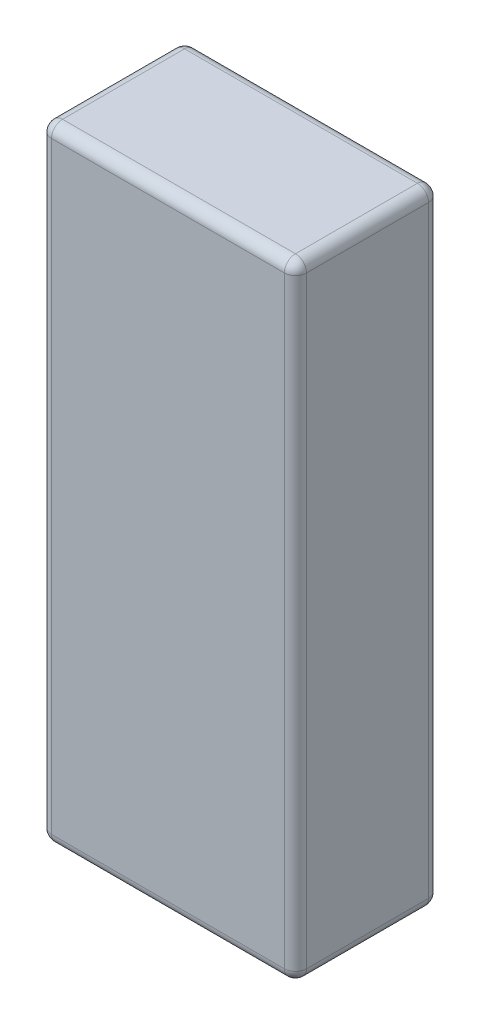
SolidWorks part; units mm, degrees
ref_plane "Front Plane" through (0, 0, 0) normal (0, 0, 1) x (1, 0, 0)
ref_plane "Top Plane" through (0, 0, 0) normal (0, 1, 0) x (1, 0, 0)
ref_plane "Right Plane" through (0, 0, 0) normal (1, 0, 0) x (0, 0, -1)
sketch "Sketch1" plane through (0, 0, 0) normal (0, 0, 1) x (1, 0, 0)
  line L1 (-34.5, -84.5) -> (34.5, -84.5)
  line L2 (-34.5, -84.5) -> (-34.5, 84.5)
  line L3 (-34.5, 84.5) -> (34.5, 84.5)
  line L4 (34.5, -84.5) -> (34.5, 84.5)
  line L5 (-34.5, -84.5) -> (34.5, 84.5) construction
  line L6 (-34.5, 84.5) -> (34.5, -84.5) construction
  point P0 (0, 0)
  dimension "D1" = 69
  dimension "D2" = 169
extrude "Boss-Extrude1" add sketch "Sketch1" along normal mid plane 39
sketch "Sketch2" plane through (0, 0, 0) normal (1, 0, 0) x (0, 0, -1)
  line L0 (-19.5, 84.5) -> (19.5, -84.5) construction
fillet "Fillet1" radius 3 12 edges at (-34.5, 0, 19.5) (-34.5, 0, -19.5) (34.5, 0, 19.5) (34.5, 0, -19.5) (-34.5, -84.5, 0) (0, -84.5, 19.5) (34.5, -84.5, 0) (0, -84.5, -19.5) (34.5, 84.5, 0) (0, 84.5, 19.5) (-34.5, 84.5, 0) (0, 84.5, -19.5)
